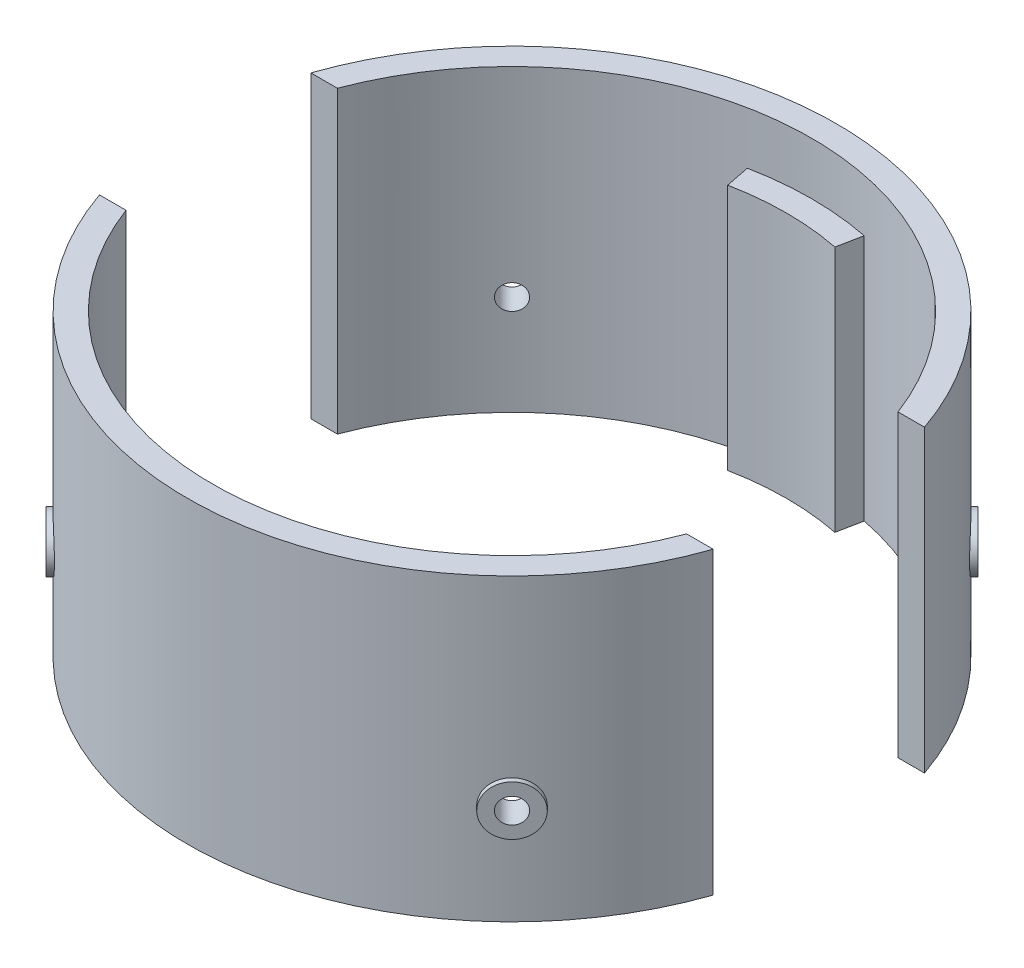
SolidWorks part; units mm, degrees
ref_plane "Front Plane" through (0, 0, 0) normal (0, 0, 1) x (1, 0, 0)
ref_plane "Top Plane" through (0, 0, 0) normal (0, 1, 0) x (1, 0, 0)
ref_plane "Right Plane" through (0, 0, 0) normal (1, 0, 0) x (0, 0, -1)
sketch "Sketch1" plane through (0, 0, 0) normal (0, 1, 0) x (1, 0, 0)
  line L0 (-44.3786, 0) -> (45.8866, 0) construction
  line L1 (-36, 12.7) -> (-36, -12.7) construction
  line L2 (-15, -36) -> (0, -36)
  line L3 (-15, -36) -> (0, -36)
  line L4 (-36.8742, 12.7) -> (-33.6855, 12.7)
  line L5 (-36.8742, -12.7) -> (-33.6855, -12.7)
  line L6 (0, 44.5416) -> (0, -51.5223) construction
  line L7 (36.8742, -12.7) -> (33.6855, -12.7)
  line L8 (36.8742, 12.7) -> (33.6855, 12.7)
  arc A0 (36.8742, 12.7) -> (-36.8742, 12.7) centre (0, 0) ccw
  arc A1 (-33.6855, -12.7) -> (33.6855, -12.7) centre (0, 0) ccw
  arc A2 (33.6855, 12.7) -> (-33.6855, 12.7) centre (0, 0) ccw
  arc A3 (-36.8742, -12.7) -> (36.8742, -12.7) centre (0, 0) ccw
  point P10 (-36, 0)
  dimension "D1" = 78
  dimension "D2" = 72
  dimension "D3" = 25.4
extrude "Boss-Extrude1" add sketch "Sketch1" along normal blind 36 contours A2 L8 A0 L4 | A1 L7 A3 L5
sketch "Sketch2" plane through (0, 0, 0) normal (0, -1, 0) x (1, 0, 0)
  line L0 (0, 41.7944) -> (0, -43.3877) construction
  line L1 (-8.8794, 44.6397) -> (9.383, -47.1716) construction
  line L2 (8.6088, 43.2795) -> (-9.9559, -50.0519) construction
  line L3 (-6.438, 32.3659) -> (-7.0233, 35.3083)
  line L4 (6.438, 32.3659) -> (7.0233, 35.3083)
  line L5 (-6.438, -32.3659) -> (-7.0233, -35.3083)
  line L6 (6.438, -32.3659) -> (7.0233, -35.3083)
  arc A0 (-7.0233, -35.3083) -> (7.0233, -35.3083) centre (0, 0) ccw
  arc A1 (-6.438, -32.3659) -> (6.438, -32.3659) centre (0, 0) ccw
  arc A2 (6.438, 32.3659) -> (-6.438, 32.3659) centre (0, 0) ccw
  arc A3 (7.0233, 35.3083) -> (-7.0233, 35.3083) centre (0, 0) ccw
  dimension "D1" = 72
  dimension "D2" = 3
  dimension "D3" = 11.25
  dimension "D4" = 11.25
extrude "Boss-Extrude2" add sketch "Sketch2" against normal blind 29.7
ref_plane "Plane1" through (-23.1927, 0, 23.1927) normal (-0.7071, 0, 0.7071) x (0, -1, 0)
ref_plane "Plane2" through (-26.7283, 0, 26.7283) normal (-0.7071, 0, 0.7071) x (0, -1, 0)
sketch "Sketch3" plane through (-26.7283, 0, 26.7283) normal (-0.7071, 0, 0.7071) x (0, -1, 0)
  line L0 (0, 0) -> (-36, 0) construction
  line L1 (-36, 39) -> (-36, -17.0938) construction
  line L2 (0, -17.0938) -> (0, 39) construction
  circle A0 centre (-12, 0) radius 3
  dimension "D1" = 6
  dimension "D2" = 12
extrude "Boss-Extrude3" add sketch "Sketch3" along normal blind 1.8
sketch "Sketch4" plane through (-23.1927, 0, 23.1927) normal (-0.7071, 0, 0.7071) x (0, -1, 0)
  line L0 (0, 0) -> (-36, 0) construction
  line L1 (-36, 39) -> (-36, -17.0938) construction
  line L2 (0, -17.0938) -> (0, 39) construction
  circle A0 centre (-12, 0) radius 1.5
  dimension "D1" = 3
  dimension "D2" = 12
extrude "Cut-Extrude1" cut sketch "Sketch4" along normal through all
pattern_circular "CirPattern1" count 4 over 360 about axis through (0, 36, 0) along (0, -1, 0) of "Boss-Extrude3", "Cut-Extrude1"
ref_plane "Plane3" through (-23.1927, 0, -23.1927) normal (0.7071, 0, 0.7071) x (0, -1, 0)
ref_plane "Plane4" through (-26.7283, 0, -26.7283) normal (0.7071, 0, 0.7071) x (0, -1, 0)
sketch "Sketch5" plane through (-26.7283, 0, -26.7283) normal (0.7071, 0, 0.7071) x (0, -1, 0)
  line L0 (0, 0) -> (-36, 0) construction
  line L1 (-36, 17.0938) -> (-36, -39) construction
  circle A0 centre (-12, 0) radius 3
  dimension "D1" = 6
extrude "Boss-Extrude4" add sketch "Sketch5" against normal blind 1.8
sketch "Sketch6" plane through (-23.1927, 0, -23.1927) normal (0.7071, 0, 0.7071) x (0, -1, 0)
  line L0 (0, 0) -> (-36, 0) construction
  line L1 (-36, 17.0938) -> (-36, -39) construction
  line L2 (0, -39) -> (0, 17.0938) construction
  circle A0 centre (-12, 0) radius 1.5
  dimension "D1" = 3
  dimension "D2" = 12
extrude "Cut-Extrude2" cut sketch "Sketch6" against normal through all
pattern_circular "CirPattern3" count 4 every 90 about axis through (0, 36, 0) along (0, -1, 0) of "Boss-Extrude4", "Cut-Extrude2"
